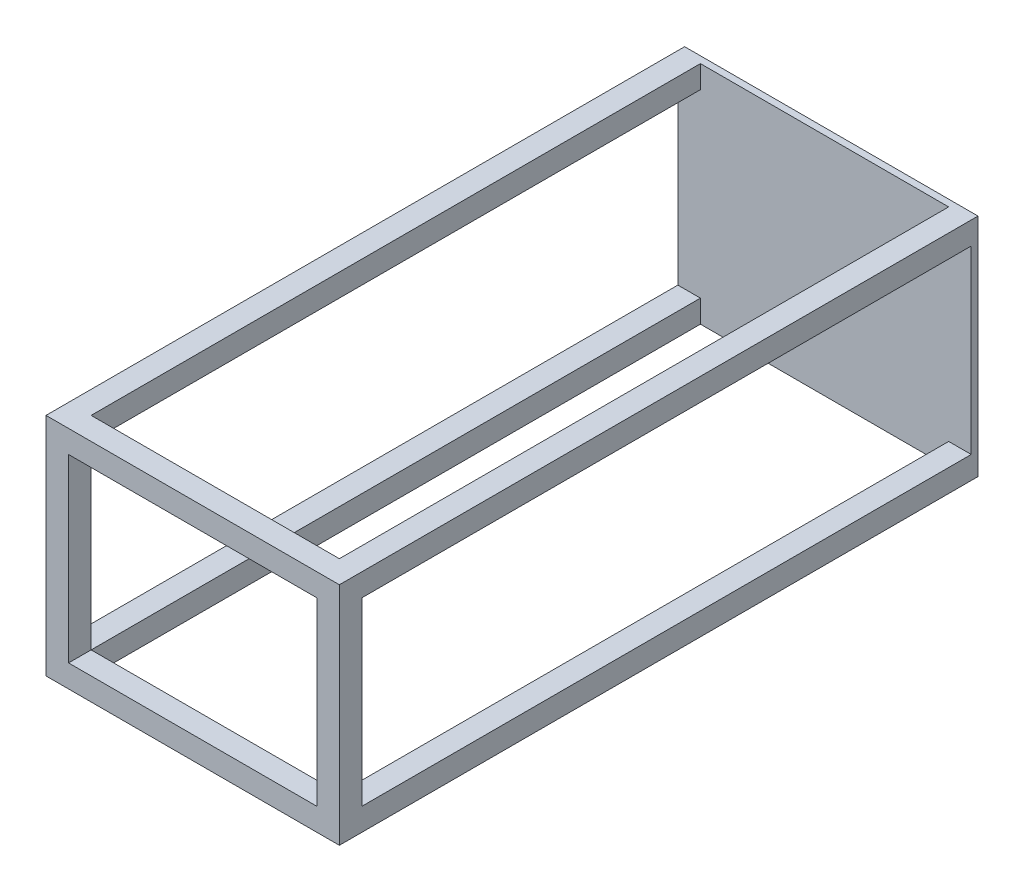
SolidWorks part; units mm, degrees
ref_plane "Front Plane" through (0, 0, 0) normal (0, 0, 1) x (1, 0, 0)
ref_plane "Top Plane" through (0, 0, 0) normal (0, 1, 0) x (1, 0, 0)
ref_plane "Right Plane" through (0, 0, 0) normal (1, 0, 0) x (0, 0, -1)
sketch "Sketch1" plane through (0, 0, 0) normal (0, 0, 1) x (1, 0, 0)
  line L1 (0, 0) -> (130, 0)
  line L2 (0, 0) -> (0, 100)
  line L3 (0, 100) -> (130, 100)
  line L4 (130, 0) -> (130, 100)
  dimension "D1" = 100
  dimension "D2" = 130
extrude "Boss-Extrude1" add sketch "Sketch1" along normal blind 3
sketch "Sketch2" plane through (0, 0, 3) normal (0, 0, 1) x (1, 0, 0)
  line L0 (130, 100) -> (0, 100) construction
  line L1 (130, 100) -> (120, 100)
  line L2 (130, 100) -> (130, 90)
  line L3 (130, 90) -> (120, 90)
  line L4 (120, 100) -> (120, 90)
  line L5 (130, 0) -> (130, 100) construction
  line L7 (130, 0) -> (120, 0)
  line L8 (130, 0) -> (130, 10)
  line L9 (130, 10) -> (120, 10)
  line L10 (120, 0) -> (120, 10)
  line L11 (0, 0) -> (10, 0)
  line L12 (0, 0) -> (0, 10)
  line L13 (0, 10) -> (10, 10)
  line L14 (10, 0) -> (10, 10)
  line L15 (0, 100) -> (10, 100)
  line L16 (0, 100) -> (0, 90)
  line L17 (0, 90) -> (10, 90)
  line L18 (10, 100) -> (10, 90)
  line L19 (129, 99) -> (122, 99)
  line L20 (129, 99) -> (129, 92)
  line L21 (129, 92) -> (122, 92)
  line L22 (122, 99) -> (122, 92)
  line L23 (122, 8) -> (129, 8)
  line L24 (122, 8) -> (122, 1)
  line L25 (122, 1) -> (129, 1)
  line L26 (129, 8) -> (129, 1)
  line L27 (9, 8) -> (2, 8)
  line L28 (9, 8) -> (9, 1)
  line L29 (9, 1) -> (2, 1)
  line L30 (2, 8) -> (2, 1)
  line L31 (8, 99) -> (1, 99)
  line L32 (8, 99) -> (8, 92)
  line L33 (8, 92) -> (1, 92)
  line L34 (1, 99) -> (1, 92)
  point P39 (10, 5)
  point P40 (4.5, 92)
  dimension "D1" = 10
  dimension "D2" = 10
  dimension "D3" = 10
  dimension "D4" = 10
  dimension "D5" = 10
  dimension "D6" = 10
  dimension "D7" = 10
  dimension "D8" = 10
  dimension "D9" = 7
  dimension "D10" = 7
  dimension "D11" = 7
  dimension "D12" = 7
  dimension "D13" = 7
  dimension "D14" = 7
  dimension "D15" = 7
  dimension "D16" = 7
  dimension "D17" = 1
  dimension "D18" = 2
  dimension "D19" = 1
  dimension "D20" = 2
  dimension "D21" = 2
  dimension "D22" = 2
  dimension "D23" = 2
  dimension "D24" = 2
  dimension "D25" = 2
extrude "Boss-Extrude2" add sketch "Sketch2" along normal blind 280
sketch "Sketch3" plane through (120, 0, 0) normal (-1, 0, 0) x (0, 0, 1)
  line L0 (283, 90) -> (3, 90) construction
  line L1 (283, 100) -> (273, 100)
  line L2 (283, 100) -> (283, 90)
  line L3 (283, 90) -> (273, 90)
  line L4 (273, 100) -> (273, 90)
  line L6 (274.5, 91.5) -> (281.5, 91.5)
  line L7 (274.5, 91.5) -> (274.5, 98.5)
  line L8 (274.5, 98.5) -> (281.5, 98.5)
  line L9 (281.5, 91.5) -> (281.5, 98.5)
  dimension "D1" = 10
  dimension "D2" = 1.5
  dimension "D3" = 1.5
  dimension "D4" = 1.5
  dimension "D5" = 1.5
extrude "Boss-Extrude3" add sketch "Sketch3" along normal blind 112
sketch "Sketch4" plane through (120, 0, 0) normal (-1, 0, 0) x (0, 0, 1)
  line L0 (283, 0) -> (0, 0) construction
  line L1 (283, 10) -> (273, 10)
  line L2 (283, 10) -> (283, 0)
  line L3 (283, 0) -> (273, 0)
  line L4 (273, 10) -> (273, 0)
  line L6 (274.5, 1.5) -> (281.5, 1.5)
  line L7 (274.5, 1.5) -> (274.5, 8.5)
  line L8 (274.5, 8.5) -> (281.5, 8.5)
  line L9 (281.5, 1.5) -> (281.5, 8.5)
  dimension "D1" = 10
  dimension "D2" = 1.5
  dimension "D3" = 1.5
  dimension "D4" = 1.5
  dimension "D5" = 1.5
extrude "Boss-Extrude4" add sketch "Sketch4" along normal blind 112
sketch "Sketch5" plane through (0, 10, 0) normal (0, 1, 0) x (1, 0, 0)
  line L1 (120, -273) -> (130, -273)
  line L2 (120, -273) -> (120, -283)
  line L3 (120, -283) -> (130, -283)
  line L4 (130, -273) -> (130, -283)
  line L5 (121.5, -274.5) -> (128.5, -274.5)
  line L6 (121.5, -274.5) -> (121.5, -281.5)
  line L7 (121.5, -281.5) -> (128.5, -281.5)
  line L8 (128.5, -274.5) -> (128.5, -281.5)
  dimension "D1" = 1.5
  dimension "D2" = 1.5
  dimension "D3" = 1.5
  dimension "D4" = 1.5
extrude "Boss-Extrude5" add sketch "Sketch5" along normal blind 82
sketch "Sketch6" plane through (0, 90, 0) normal (0, -1, 0) x (1, 0, 0)
  line L1 (10, 273) -> (0, 273)
  line L2 (10, 273) -> (10, 283)
  line L3 (10, 283) -> (0, 283)
  line L4 (0, 273) -> (0, 283)
  line L5 (1.5, 281.5) -> (8.5, 281.5)
  line L6 (1.5, 281.5) -> (1.5, 274.5)
  line L7 (1.5, 274.5) -> (8.5, 274.5)
  line L8 (8.5, 281.5) -> (8.5, 274.5)
  dimension "D1" = 1.5
  dimension "D2" = 1.5
  dimension "D3" = 1.5
  dimension "D4" = 1.5
extrude "Boss-Extrude6" add sketch "Sketch6" along normal blind 82
sketch "Sketch7" plane through (0, 0, 283) normal (0, 0, 1) x (1, 0, 0)
  line L0 (129, 92) -> (129, 99) construction
  line L1 (1, 92) -> (8, 92)
  line L2 (1, 92) -> (1, 99)
  line L3 (1, 99) -> (8, 99)
  line L4 (8, 92) -> (8, 99)
  line L5 (122, 92) -> (129, 92)
  line L6 (122, 92) -> (122, 99)
  line L7 (122, 99) -> (129, 99)
  line L8 (129, 92) -> (129, 99)
  line L9 (129, 92) -> (129, 99) construction
  line L10 (129, 1) -> (129, 8) construction
  line L11 (122, 8) -> (129, 8)
  line L12 (122, 8) -> (122, 1)
  line L13 (122, 1) -> (129, 1)
  line L14 (129, 8) -> (129, 1)
  line L16 (8, 8) -> (2, 8)
  line L17 (8, 8) -> (8, 1)
  line L18 (8, 1) -> (2, 1)
  line L19 (2, 8) -> (2, 1)
extrude "Boss-Extrude7" add sketch "Sketch7" against normal blind 0.1
